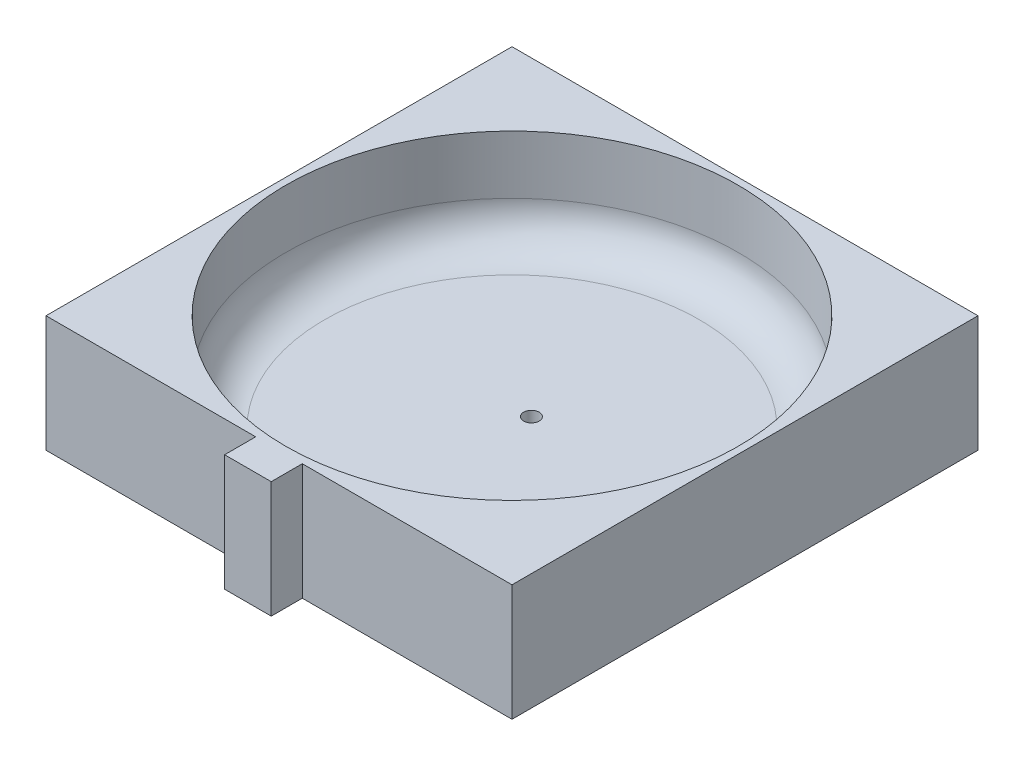
SolidWorks part; units mm, degrees
ref_plane "前视基准面" through (0, 0, 0) normal (0, 0, 1) x (1, 0, 0)
ref_plane "上视基准面" through (0, 0, 0) normal (0, 1, 0) x (1, 0, 0)
ref_plane "右视基准面" through (0, 0, 0) normal (1, 0, 0) x (0, 0, -1)
sketch "草图1" plane through (0, 0, 0) normal (0, 1, 0) x (1, 0, 0)
  line L1 (-60, 60) -> (60, 60)
  line L2 (-60, 60) -> (-60, -60)
  line L3 (-60, -60) -> (60, -60)
  line L4 (60, 60) -> (60, -60)
  dimension "D1" = 120
  dimension "D2" = 120
  dimension "D3" = 60
  dimension "D4" = 60
extrude "凸台-拉伸1" add sketch "草图1" along normal blind 30
sketch "草图2" plane through (0, 30, 0) normal (0, 1, 0) x (1, 0, 0)
  circle A0 centre (0, 0) radius 58.252
extrude "切除-拉伸1" cut sketch "草图2" against normal blind 25
fillet "圆角1" radius 10 1 edges at (0, 5, 58.252)
sketch "草图3" plane through (0, 0, 0) normal (0, -1, 0) x (1, 0, 0)
  line L0 (-60, 60) -> (60, 60) construction
  circle A0 centre (0, -5) radius 2
  dimension "D1" = 4
  dimension "D2" = 65
extrude "切除-拉伸2" cut sketch "草图3" against normal blind 25
sketch "草图4" plane through (0, 0, 0) normal (0, -1, 0) x (1, 0, 0)
  line L0 (-60, 60) -> (60, 60) construction
  line L1 (-6, 68) -> (6, 68)
  line L2 (-6, 68) -> (-6, 60)
  line L3 (-6, 60) -> (6, 60)
  line L4 (6, 68) -> (6, 60)
  point P6 (0, 60)
  dimension "D1" = 12
  dimension "D2" = 0
  dimension "D3" = 8
extrude "凸台-拉伸2" add sketch "草图4" against normal blind 30
